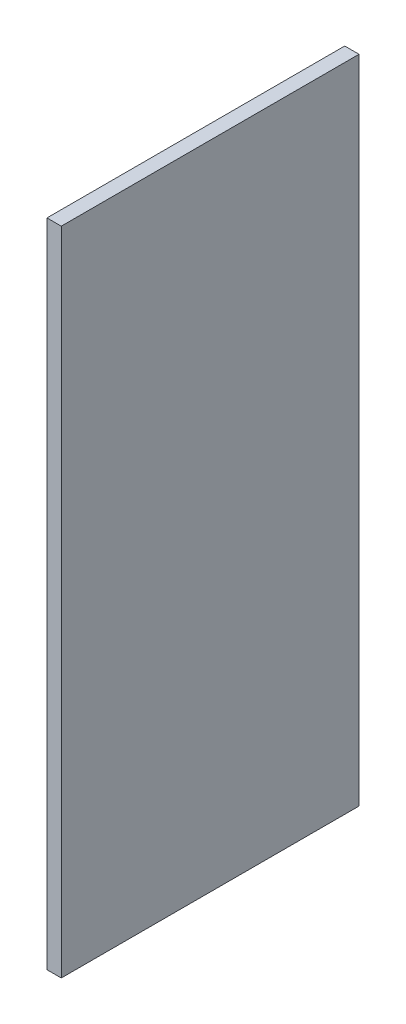
SolidWorks part; units mm, degrees
ref_plane "Alzado" through (0, 0, 0) normal (0, 0, 1) x (1, 0, 0)
ref_plane "Planta" through (0, 0, 0) normal (0, 1, 0) x (1, 0, 0)
ref_plane "Vista lateral" through (0, 0, 0) normal (1, 0, 0) x (0, 0, -1)
ref_plane "Plano_ParedGrandeOeste" through (0, 50, 0) normal (0, 1, 0) x (1, 0, 0)
sketch "SkParedGrandeOeste" plane through (0, 50, 0) normal (0, 1, 0) x (1, 0, 0)
  line L1 (-203, -187.5) -> (-185, -187.5)
  line L2 (-203, -187.5) -> (-203, 187.5)
  line L3 (-203, 187.5) -> (-185, 187.5)
  line L4 (-185, -187.5) -> (-185, 187.5)
extrude "ParedGrandeOeste" add sketch "SkParedGrandeOeste" along normal blind 820 separate body
